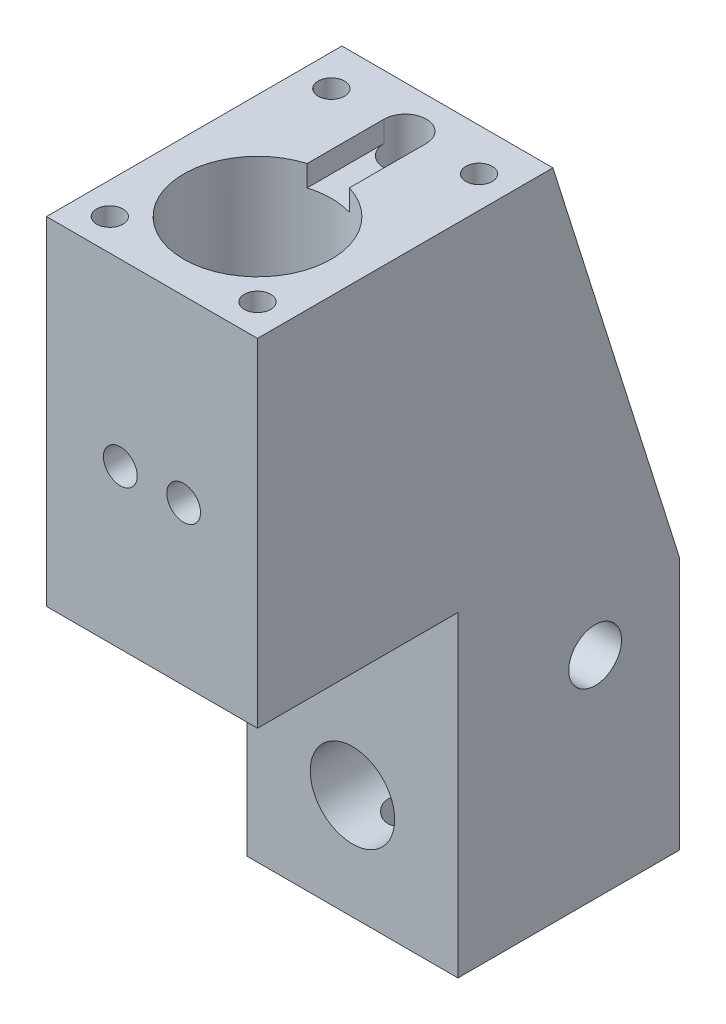
SolidWorks part; units mm, degrees
ref_plane "Front Plane" through (0, 0, 0) normal (0, 0, 1) x (1, 0, 0)
ref_plane "Top Plane" through (0, 0, 0) normal (0, 1, 0) x (1, 0, 0)
ref_plane "Right Plane" through (0, 0, 0) normal (1, 0, 0) x (0, 0, -1)
sketch "Sketch1" plane through (0, 0, 0) normal (1, 0, 0) x (0, 0, -1)
  line L0 (0, 0) -> (0, 30)
  line L1 (0, 30) -> (-19, 30)
  line L2 (-19, 30) -> (-19, 62)
  line L3 (-19, 62) -> (9, 62)
  line L4 (9, 62) -> (21, 24)
  line L5 (21, 24) -> (21, 0)
  line L6 (21, 0) -> (0, 0)
  point P3 (11.186, 62)
  dimension "D1" = 30
  dimension "D2" = 62
  dimension "D3" = 40
  dimension "D4" = 12
  dimension "D5" = 38
  dimension "D6" = 21
extrude "Boss-Extrude1" add sketch "Sketch1" along normal mid plane 20
sketch "Sketch2" plane through (0, 62, 0) normal (0, 1, 0) x (1, 0, 0)
  line L0 (0, 0) -> (0, -19) construction
  line L1 (10, -19) -> (-10, -19) construction
  circle A0 centre (0, -9) radius 7
  dimension "D1" = 14
  dimension "D2" = 10
extrude "Cut-Extrude1" cut sketch "Sketch2" against normal through all
sketch "Sketch5" plane through (0, 62, 0) normal (0, 1, 0) x (1, 0, 0)
  line L0 (0, 0) -> (0, -19) construction
  line L1 (10, -19) -> (-10, -19) construction
  point P0 (-7, -16)
  point P2 (7, -16)
  point P4 (7, 5)
  point P6 (-7, 5)
  point P17 (0, 0)
  point P18 (-6.0307, 5)
  point P19 (0, 0)
  point P20 (-7, -16)
  dimension "D1" = 14
  dimension "D2" = 24
  dimension "D3" = 3
hole_wizard "M3 Tapped Hole1" positions "Sketch5" profile "Sketch4" tap size "M3" standard "DIN"
sketch "Sketch4" plane through (-7, 62, 16) normal (1, 0, 0) x (0, 0, 1)
  line L0 (0, 0) -> (0, 9)
  line L1 (0, 9) -> (1.25, 8.2489)
  line L2 (1.25, 8.2489) -> (1.25, 0)
  line L5 (1.25, 0) -> (0, 0)
  line L10 (0, 9) -> (-1.25, 8.2489) construction
  line L11 (0, -6.35) -> (0, 107.95) construction
  dimension "Tap Drill Dia." = 2.5
  dimension "Tap Drill Depth" = 9
  dimension "Drill Angle" = 118
cosmetic thread "Hole Thread1" parameters "D1"=6, "D2"=3
cosmetic thread "Hole Thread2" parameters "D1"=6, "D2"=3
cosmetic thread "Hole Thread3" parameters "D1"=6, "D2"=3
cosmetic thread "Hole Thread4" parameters "D1"=6, "D2"=3
sketch "Sketch6" plane through (0, 62, 0) normal (0, 1, 0) x (1, 0, 0)
  line L0 (0, 5) -> (0, -4.4141) construction
  line L1 (2, 5) -> (2, -4.4141)
  line L2 (-2, 5) -> (-2, -4.4141)
  line L3 (10, -19) -> (-10, -19) construction
  arc A0 (2, 5) -> (-2, 5) centre (0, 5) ccw
  arc A1 (-2, -4.4141) -> (2, -4.4141) centre (0, -4.4141) ccw
  point P3 (0, 0.293)
  dimension "D1" = 4
  dimension "D2" = 24
extrude "Cut-Extrude2" cut sketch "Sketch6" against normal blind 2
sketch "Sketch7" plane through (0, 62, 0) normal (0, 1, 0) x (1, 0, 0)
  line L0 (10, -19) -> (-10, -19) construction
  circle A0 centre (0, 5) radius 2
  dimension "D1" = 4
  dimension "D2" = 24
extrude "Cut-Extrude3" cut sketch "Sketch7" against normal blind 30
sketch "Sketch8" plane through (0, 62, 0) normal (0, 1, 0) x (1, 0, 0)
  circle A0 centre (0, 5) radius 1.25
  dimension "D1" = 2.5
extrude "Cut-Extrude4" cut sketch "Sketch8" against normal blind 49
sketch "Sketch9" plane through (0, 0, 19) normal (0, 0, 1) x (1, 0, 0)
  line L0 (0, 62) -> (0, 45) construction
  line L1 (10, 62) -> (-10, 62) construction
  circle A0 centre (-3, 45) radius 1.6
  circle A1 centre (3, 45) radius 1.6
  point P9 (0, 0)
  dimension "D1" = 6
  dimension "D2" = 3.2
  dimension "D3" = 17
extrude "Cut-Extrude5" cut sketch "Sketch9" against normal up to next
sketch "Sketch10" plane through (10, 0, 0) normal (1, 0, 0) x (0, 0, -1)
  line L0 (21, 0) -> (13, 0) construction
  line L1 (13, 0) -> (13, 20) construction
  circle A0 centre (13, 20) radius 2.5
  dimension "D3" = 5
  dimension "D1" = 8
  dimension "D2" = 20
extrude "Cut-Extrude6" cut sketch "Sketch10" against normal through all
sketch "Sketch11" plane through (0, 0, 0) normal (0, -1, 0) x (1, 0, 0)
  line L0 (0, -21) -> (0, -13) construction
  line L1 (10, -21) -> (-10, -21) construction
  circle A0 centre (0, -13) radius 1.25
  dimension "D2" = 2.5
  dimension "D1" = 8
extrude "Cut-Extrude7" cut sketch "Sketch11" against normal up to next
sketch "Sketch12" plane through (0, 0, 0) normal (0, 0, 1) x (1, 0, 0)
  circle A0 centre (0, 10) radius 4
  dimension "D2" = 8
  dimension "D1" = 10
extrude "Cut-Extrude8" cut sketch "Sketch12" against normal up to next
sketch "Sketch15" plane through (0, 0, 0) normal (0, -1, 0) x (-1, 0, 0)
  point P0 (0, 13)
  point P3 (0, 5)
  dimension "D1" = 8
hole_wizard "M4 Tapped Hole1" positions "Sketch15" profile "Sketch14" tap size "M4" standard "DIN"
sketch "Sketch14" plane through (0, 0, -13) normal (1, 0, 0) x (0, 0, -1)
  line L0 (0, 0) -> (0, 10)
  line L1 (0, 10) -> (1.65, 9.0086)
  line L2 (1.65, 9.0086) -> (1.65, 0)
  line L5 (1.65, 0) -> (0, 0)
  line L10 (0, 10) -> (-1.65, 9.0086) construction
  line L11 (0, -6.35) -> (0, 107.95) construction
  dimension "Tap Drill Dia." = 3.3
  dimension "Tap Drill Depth" = 10
  dimension "Drill Angle" = 118
cosmetic thread "Hole Thread5" parameters "D1"=8, "D2"=4
cosmetic thread "Hole Thread6" parameters "D1"=8, "D2"=4
